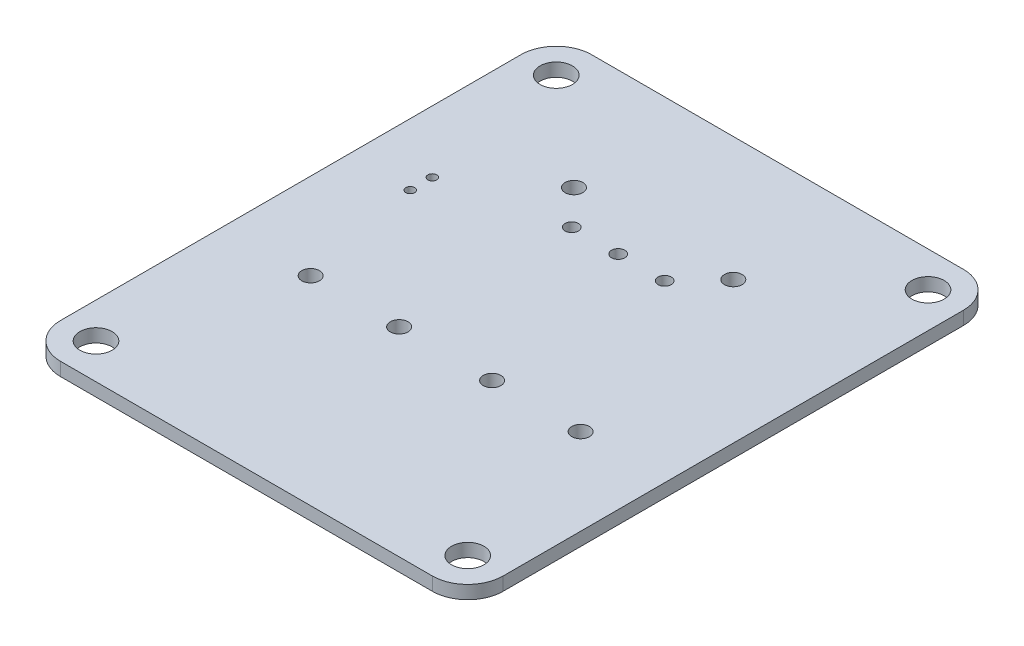
SolidWorks part; units mm, degrees
ref_plane "Front" through (0, 0, 0) normal (0, 0, 1) x (1, 0, 0)
ref_plane "Top" through (0, 0, 0) normal (0, 1, 0) x (1, 0, 0)
ref_plane "Right" through (0, 0, 0) normal (1, 0, 0) x (0, 0, -1)
sketch "Sketch1" plane through (0, 0, 0) normal (0, 1, 0) x (1, 0, 0)
  line L0 (0, 30) -> (0, 0) construction
  line L1 (-21, 30) -> (21, 30)
  line L2 (-25, 26) -> (-25, -26)
  line L3 (-21, -30) -> (21, -30)
  line L4 (25, 26) -> (25, -26)
  line L5 (0, 0) -> (25, 0) construction
  circle A0 centre (-21, 26) radius 1.825
  circle A1 centre (21, 26) radius 1.825
  circle A2 centre (21, -26) radius 1.825
  circle A3 centre (-21, -26) radius 1.825
  arc A4 (-25, -26) -> (-21, -30) centre (-21, -26) ccw
  arc A5 (21, -30) -> (25, -26) centre (21, -26) ccw
  arc A6 (21, 30) -> (25, 26) centre (21, 26) cw
  arc A7 (-21, 30) -> (-25, 26) centre (-21, 26) ccw
  dimension "D4" = 3.65
  dimension "D1" = 50
  dimension "D2" = 60
  dimension "D3" = 42
extrude "Boss-Extrude1" add sketch "Sketch1" along normal blind 1.5
sketch "Sketch2" plane through (0, 1.5, 0) normal (0, 1, 0) x (1, 0, 0)
  line L0 (0, 30) -> (0, -30) construction
  line L1 (21, 30) -> (-21, 30) construction
  line L2 (-21, -30) -> (21, -30) construction
  line L3 (-15.25, -7.5) -> (-5.25, -7.5) construction
  line L5 (-25, 26) -> (-25, -26) construction
  circle A0 centre (-9, 16) radius 1
  circle A1 centre (9, 16) radius 1
  circle A2 centre (-5.25, 12) radius 0.75
  circle A3 centre (0, 12) radius 0.75
  circle A4 centre (5.25, 12) radius 0.75
  circle A5 centre (-15.25, -7.5) radius 1
  circle A6 centre (-5.25, -7.5) radius 1
  circle A7 centre (5.25, -7.5) radius 1
  circle A8 centre (15.25, -7.5) radius 1
  circle A9 centre (-18, 9) radius 0.5
  circle A10 centre (-18, 6.5) radius 0.5
  dimension "D3" = 2
  dimension "D6" = 1.5
  dimension "D9" = 2
  dimension "D13" = 1
  dimension "D1" = 14
  dimension "D2" = 18
  dimension "D4" = 4
  dimension "D5" = 10.5
  dimension "D7" = 22.5
  dimension "D8" = 10
  dimension "D10" = 21
  dimension "D11" = 7
  dimension "D12" = 2.5
  dimension "D14" = 10.5
extrude "Cut-Extrude1" cut sketch "Sketch2" against normal up to next
